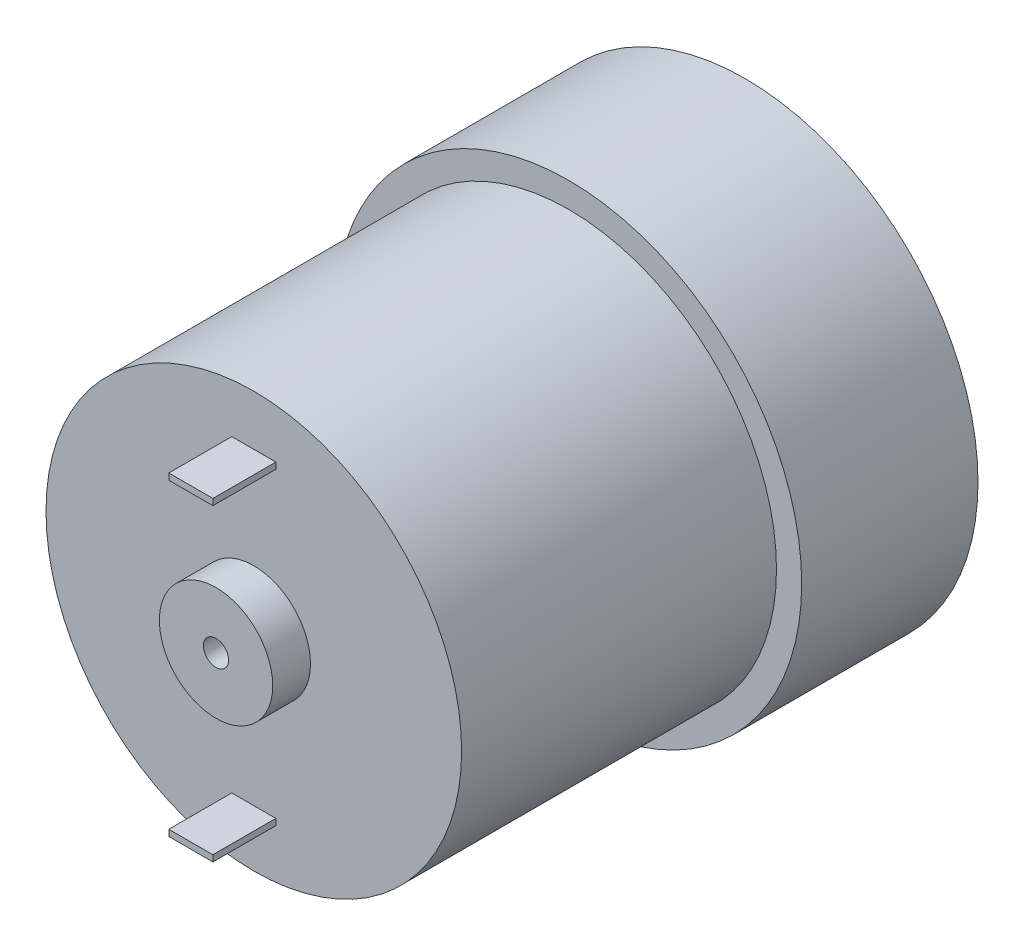
SolidWorks part; units mm, degrees
material "6063-O"
ref_plane "Front Plane" through (0, 0, 0) normal (0, 0, 1) x (1, 0, 0)
ref_plane "Top Plane" through (0, 0, 0) normal (0, 1, 0) x (1, 0, 0)
ref_plane "Right Plane" through (0, 0, 0) normal (1, 0, 0) x (0, 0, -1)
sketch "Sketch1" plane through (0, 0, 0) normal (0, 0, 1) x (1, 0, 0)
  circle A0 centre (0, 0) radius 18.5
  dimension "D1" = 37
extrude "Boss-Extrude1" add sketch "Sketch1" along normal blind 42
sketch "Sketch2" plane through (0, 0, 42) normal (0, 0, 1) x (1, 0, 0)
  circle A0 centre (0, 0) radius 18.5
  circle A1 centre (0, 0) radius 18.5 construction
  circle A2 centre (0, 0) radius 4.5
  dimension "D1" = 9
extrude "Cut-Extrude1" cut sketch "Sketch2" against normal blind 3
sketch "Sketch3" plane through (0, 0, 39) normal (0, 0, 1) x (1, 0, 0)
  circle A0 centre (0, 0) radius 18.5
  circle A1 centre (0, 0) radius 18.5 construction
  circle A2 centre (0, 0) radius 16.5
  circle M4 centre (0, 0) radius 18.5
  dimension "D1" = 33
extrude "Cut-Extrude4" cut sketch "Sketch3" against normal blind 25 contours A2 M4
sketch "Sketch4" plane through (0, 0, 0) normal (0, 0, -1) x (-1, 0, 0)
  line L0 (0, 0) -> (0, -18.5) construction
  circle A0 centre (0, 0) radius 18.5 construction
  circle A1 centre (0, -7) radius 6
  dimension "D2" = 12
  dimension "D1" = 7
extrude "Boss-Extrude2" add sketch "Sketch4" along normal blind 4.6
fillet "Fillet1" radius 0.5 1 edges at (-6, -7, -4.6)
sketch "Sketch5" plane through (0, 0, -4.6) normal (0, 0, -1) x (-1, 0, 0)
  circle A0 centre (0, -7) radius 3
  dimension "D1" = 6
extrude "Cut-Extrude5" cut sketch "Sketch5" against normal blind 10
sketch "Sketch6" plane through (0, 0, 42) normal (0, 0, 1) x (1, 0, 0)
  circle A0 centre (0, 0) radius 1
  dimension "D1" = 2
extrude "Cut-Extrude6" cut sketch "Sketch6" against normal blind 10
sketch "Sketch7" plane through (0, 0, 39) normal (0, 0, 1) x (1, 0, 0)
  line L0 (0, -16.5) -> (0, 16.5) construction
  line L2 (1.75, 12) -> (-1.75, 12)
  line L3 (1.75, 12) -> (1.75, 12.5)
  line L4 (1.75, 12.5) -> (-1.75, 12.5)
  line L5 (-1.75, 12) -> (-1.75, 12.5)
  line L6 (1.75, 12) -> (-1.75, 12.5) construction
  line L7 (1.75, 12.5) -> (-1.75, 12) construction
  line L8 (-1.75, -12) -> (1.75, -12)
  line L9 (-1.75, -12) -> (-1.75, -12.5)
  line L10 (-1.75, -12.5) -> (1.75, -12.5)
  line L11 (1.75, -12) -> (1.75, -12.5)
  line L12 (-1.75, -12) -> (1.75, -12.5) construction
  line L13 (-1.75, -12.5) -> (1.75, -12) construction
  circle A0 centre (0, 0) radius 16.5 construction
  point P5 (0, 12.25)
  point P10 (0, -12.25)
  dimension "D1" = 3.5
  dimension "D2" = 0.5
  dimension "D3" = 12
  dimension "D4" = 12
extrude "Boss-Extrude3" add sketch "Sketch7" along normal blind 5
sketch "Sketch8" plane through (0, 0, 0) normal (0, 0, -1) x (-1, 0, 0)
  line L0 (0, 0) -> (15.5, 0) construction
  line L1 (0, 0) -> (-15.5, 0) construction
  line L2 (0, 0) -> (-7.75, 13.4234) construction
  line L3 (0, 0) -> (-7.75, -13.4234) construction
  line L4 (-13.8293, -7) -> (13.8293, -7) construction
  circle A0 centre (0, 0) radius 15.5 construction
  circle A1 centre (-7.75, 13.4234) radius 1.5
  circle A2 centre (15.5, 0) radius 1.75
  circle A3 centre (-7.75, -13.4234) radius 1.5
  circle A4 centre (-13.8293, -7) radius 1.5
  circle A5 centre (-15.5, 0) radius 1.75
  circle A6 centre (13.8293, -7) radius 1.5
  circle A7 centre (0, 15.5) radius 1.75
  point P15 (0, -7)
  dimension "D1" = 31
  dimension "D4" = 3
  dimension "D5" = 3.5
  dimension "D2" = 120
  dimension "D3" = 120
hole_wizard "M3x0.5 Tapped Hole1" positions "Sketch9" profile "Sketch10" tap size "M3x0.5" standard "ANSI Metric"
sketch "Sketch9" plane through (0, 0, 0) normal (0, 0, -1) x (-1, 0, 0)
  point P17 (15.5, 0)
  point P20 (-7.75, 13.4234)
  point P23 (-7.75, -13.4234)
  point P26 (-15.5, 0)
sketch "Sketch10" plane through (-15.5, 0, 0) normal (1, 0, 0) x (0, 1, 0)
  line L0 (0, 0) -> (0, 8.2511)
  line L1 (0, 8.2511) -> (1.25, 7.5)
  line L2 (1.25, 7.5) -> (1.25, 0)
  line L5 (1.25, 0) -> (0, 0)
  line L10 (0, 8.2511) -> (-1.25, 7.5) construction
  line L11 (0, -6.35) -> (0, 107.95) construction
  dimension "Tap Drill Dia." = 2.5
  dimension "Tap Drill Depth" = 7.5
  dimension "Drill Angle" = 118
cosmetic thread "Hole Thread1" parameters "D1"=6, "D2"=3
cosmetic thread "Hole Thread2" parameters "D1"=6, "D2"=3
cosmetic thread "Hole Thread3" parameters "D1"=6, "D2"=3
cosmetic thread "Hole Thread4" parameters "D1"=6, "D2"=3
hole_wizard "Ø3.0mm Dowel Hole1" positions "Sketch11" profile "Sketch12" hole size "Ø3.0" standard "ANSI Metric"
sketch "Sketch11" plane through (0, 0, 0) normal (0, 0, -1) x (-1, 0, 0)
  point P3 (0, 15.5)
  point P12 (-13.8293, -7)
  point P15 (13.8293, -7)
sketch "Sketch12" plane through (0, 15.5, 0) normal (1, 0, 0) x (0, 1, 0)
  line L0 (0, 0) -> (0, 8.4013)
  line L1 (0, 8.4013) -> (1.5, 7.5)
  line L2 (1.5, 7.5) -> (1.5, 0)
  line L5 (1.5, 0) -> (0, 0)
  line L10 (0, 8.4013) -> (-1.5, 7.5) construction
  line L11 (0, -6.35) -> (0, 107.95) construction
  dimension "Hole Dia." = 3
  dimension "Hole Depth" = 7.5
  dimension "Drill Angle" = 118
equation "\"D4@Sketch7\"=\"D3@Sketch7\""
